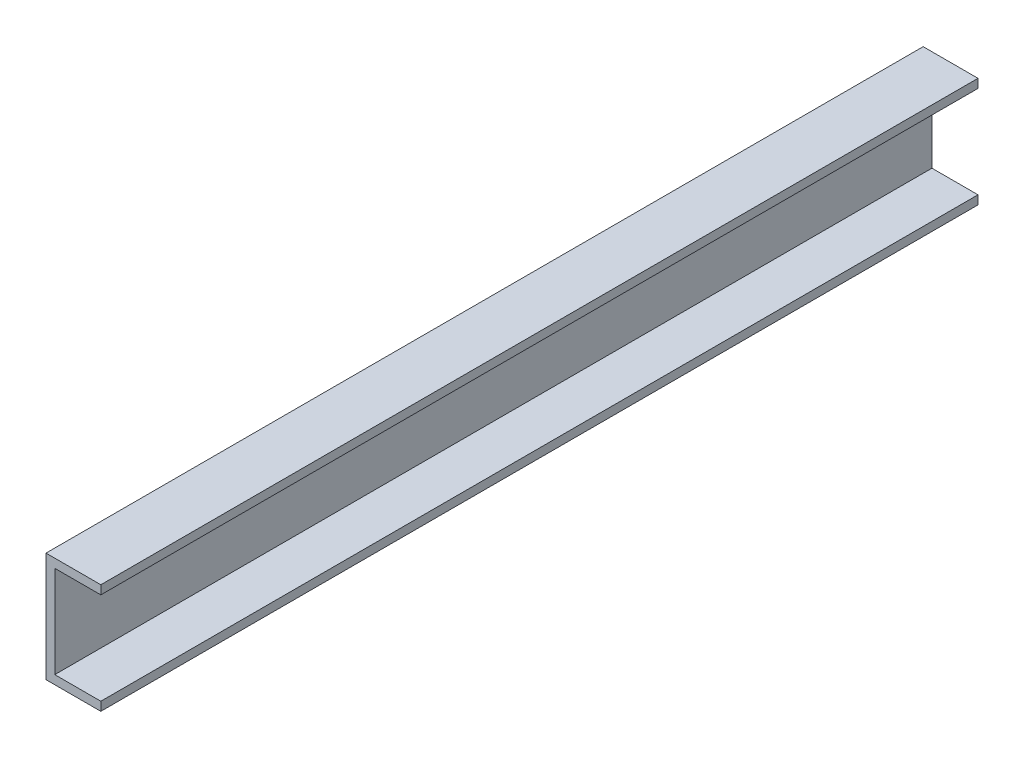
SolidWorks part; units mm, degrees
ref_plane "Front Plane" through (0, 0, 0) normal (0, 0, 1) x (1, 0, 0)
ref_plane "Top Plane" through (0, 0, 0) normal (0, 1, 0) x (1, 0, 0)
ref_plane "Right Plane" through (0, 0, 0) normal (1, 0, 0) x (0, 0, -1)
sketch "Sketch1" plane through (0, 0, 0) normal (0, 0, 1) x (1, 0, 0)
  line L0 (0, 0) -> (0, 100)
  line L1 (0, 100) -> (50, 100)
  line L2 (50, 100) -> (50, 92)
  line L3 (50, 92) -> (8, 92)
  line L4 (8, 92) -> (8, 8)
  line L5 (8, 8) -> (50, 8)
  line L6 (50, 8) -> (50, 0)
  line L7 (50, 0) -> (0, 0)
  dimension "D1" = 100
  dimension "D2" = 50
  dimension "D3" = 8
  dimension "D4" = 8
extrude "Boss-Extrude1" add sketch "Sketch1" along normal blind 800
